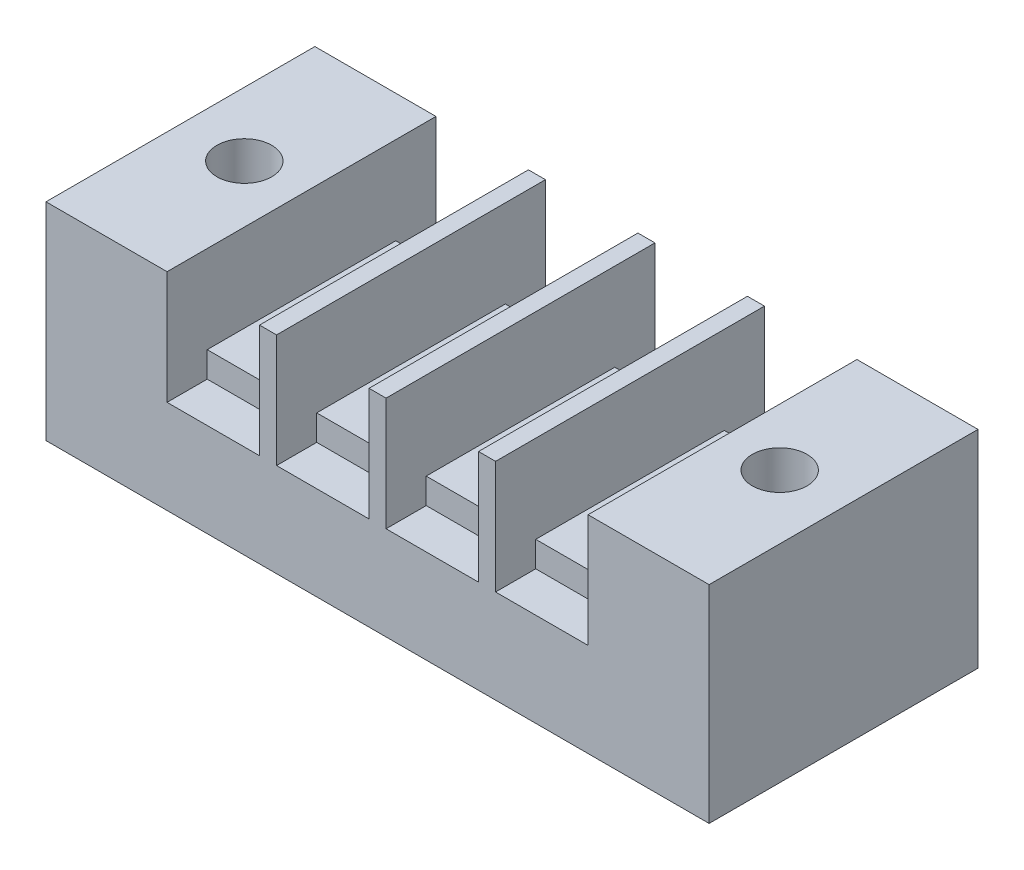
SolidWorks part; units mm, degrees
ref_plane "正面" through (0, 0, 0) normal (0, 0, 1) x (1, 0, 0)
ref_plane "平面" through (0, 0, 0) normal (0, 1, 0) x (1, 0, 0)
ref_plane "右側面" through (0, 0, 0) normal (1, 0, 0) x (0, 0, -1)
sketch "ｽｹｯﾁ1" plane through (0, 0, 0) normal (0, 1, 0) x (1, 0, 0)
  line L0 (0, 11.05) -> (0, -11.05) construction
  line L1 (-27.25, 11.05) -> (27.25, 11.05)
  line L2 (-27.25, 11.05) -> (-27.25, -11.05)
  line L3 (-27.25, -11.05) -> (27.25, -11.05)
  line L4 (27.25, 11.05) -> (27.25, -11.05)
  line L5 (-27.25, 11.05) -> (27.25, -11.05) construction
  line L6 (-27.25, -11.05) -> (27.25, 11.05) construction
  line L7 (27.25, 0) -> (-27.25, 0) construction
  circle A0 centre (-22, 0) radius 2.25
  circle A1 centre (22, 0) radius 2.25
  point P0 (0, 0)
  dimension "D3" = 4.5
  dimension "D1" = 54.5
  dimension "D2" = 22.1
  dimension "D4" = 22
extrude "ﾎﾞｽ - 押し出し1" add sketch "ｽｹｯﾁ1" along normal blind 17
sketch "ｽｹｯﾁ2" plane through (0, 17, 0) normal (0, 1, 0) x (1, 0, 0)
  line L0 (27.25, 0) -> (-27.25, 0) construction
  line L1 (27.25, -11.05) -> (27.25, 11.05) construction
  line L2 (-27.25, 11.05) -> (-27.25, -11.05) construction
  line L3 (0, 11.05) -> (0, -11.05) construction
  line L4 (27.25, 11.05) -> (-27.25, 11.05) construction
  line L5 (-27.25, -11.05) -> (27.25, -11.05) construction
  line L6 (17.3, -11.05) -> (9.7, -11.05)
  line L7 (-17.3, 11.05) -> (-9.7, 11.05)
  line L8 (-17.3, 11.05) -> (-17.3, -11.05)
  line L9 (-17.3, -11.05) -> (-9.7, -11.05)
  line L10 (-9.7, 11.05) -> (-9.7, -11.05)
  line L11 (-17.3, 11.05) -> (-9.7, -11.05) construction
  line L12 (-17.3, -11.05) -> (-9.7, 11.05) construction
  line L13 (-8.3, 11.05) -> (-0.7, 11.05)
  line L14 (-8.3, 11.05) -> (-8.3, -11.05)
  line L15 (-8.3, -11.05) -> (-0.7, -11.05)
  line L16 (-0.7, 11.05) -> (-0.7, -11.05)
  line L17 (-8.3, 11.05) -> (-0.7, -11.05) construction
  line L18 (-8.3, -11.05) -> (-0.7, 11.05) construction
  line L19 (9.7, 11.05) -> (9.7, -11.05)
  line L20 (17.3, 11.05) -> (9.7, 11.05)
  line L21 (17.3, 11.05) -> (17.3, -11.05)
  line L22 (8.3, -11.05) -> (0.7, -11.05)
  line L23 (0.7, 11.05) -> (0.7, -11.05)
  line L24 (8.3, 11.05) -> (0.7, 11.05)
  line L25 (8.3, 11.05) -> (8.3, -11.05)
  point P12 (-13.5, 0)
  point P17 (-4.5, 0)
  dimension "D1" = 7.6
  dimension "D3" = 13.5
  dimension "D2" = 9
extrude "ｶｯﾄ - 押し出し1" cut sketch "ｽｹｯﾁ2" against normal blind 7.2
sketch "ｽｹｯﾁ3" plane through (0, 9.8, 0) normal (0, 1, 0) x (1, 0, 0)
  line L0 (8.3, -11.05) -> (8.3, 11.05) construction
  line L1 (0.7, 11.05) -> (8.3, 11.05)
  line L2 (0.7, 11.05) -> (0.7, 7.75)
  line L3 (0.7, 7.75) -> (8.3, 7.75)
  line L4 (8.3, 11.05) -> (8.3, 7.75)
  line L5 (17.3, -11.05) -> (17.3, 11.05) construction
  line L6 (9.7, 11.05) -> (17.3, 11.05)
  line L7 (9.7, 11.05) -> (9.7, 7.75)
  line L8 (9.7, 7.75) -> (17.3, 7.75)
  line L9 (17.3, 11.05) -> (17.3, 7.75)
  dimension "D1" = 3.3
extrude "ｶｯﾄ - 押し出し2" cut sketch "ｽｹｯﾁ3" against normal blind 2.1
mirror "ﾐﾗｰ1" about plane through (0, 0, 0) normal (1, 0, 0) of "ｶｯﾄ - 押し出し2"
mirror "ﾐﾗｰ2" about plane through (0, 0, 0) normal (0, 0, 1) of "ﾐﾗｰ1", "ｶｯﾄ - 押し出し2"
sketch "ｽｹｯﾁ4" plane through (0, 9.8, 0) normal (0, 1, 0) x (1, 0, 0)
  line L0 (17.3, 0) -> (9.7, 0) construction
  line L1 (17.3, -11.05) -> (17.3, 11.05) construction
  line L2 (9.7, 11.05) -> (9.7, -11.05) construction
  line L3 (13.5, 7.75) -> (13.5, 0) construction
  line L4 (9.7, 7.75) -> (17.3, 7.75) construction
  circle A0 centre (13.5, 4) radius 1.75
  circle A1 centre (4.5, 4) radius 1.75
  circle A2 centre (-4.5, 4) radius 1.75
  circle A3 centre (-13.5, 4) radius 1.75
  circle A4 centre (13.5, -4) radius 1.75
  circle A5 centre (4.5, -4) radius 1.75
  circle A6 centre (-4.5, -4) radius 1.75
  circle A7 centre (-13.5, -4) radius 1.75
  dimension "D1" = 3.5
  dimension "D3" = 4
  dimension "D2" = 4
extrude "ｶｯﾄ - 押し出し3" cut sketch "ｽｹｯﾁ4" against normal blind 5
